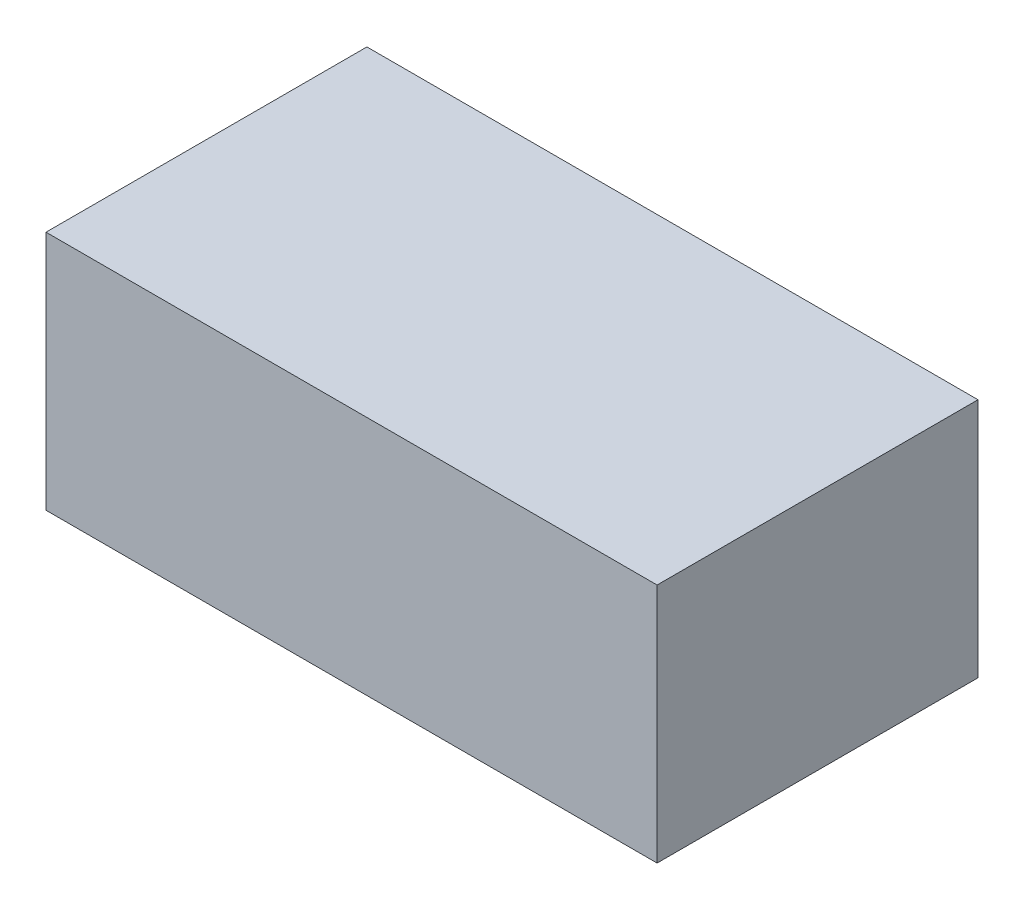
SolidWorks part; units mm, degrees
ref_plane "Plan de face" through (0, 0, 0) normal (0, 0, 1) x (1, 0, 0)
ref_plane "Plan de dessus" through (0, 0, 0) normal (0, 1, 0) x (1, 0, 0)
ref_plane "Plan de droite" through (0, 0, 0) normal (1, 0, 0) x (0, 0, -1)
sketch "Esquisse1" plane through (0, 0, 0) normal (0, 1, 0) x (1, 0, 0)
  line L1 (5.075, -2.665) -> (-5.075, -2.665)
  line L2 (5.075, -2.665) -> (5.075, 2.665)
  line L3 (5.075, 2.665) -> (-5.075, 2.665)
  line L4 (-5.075, -2.665) -> (-5.075, 2.665)
  line L5 (5.075, -2.665) -> (-5.075, 2.665) construction
  line L6 (5.075, 2.665) -> (-5.075, -2.665) construction
  point P0 (0, 0)
  dimension "D1" = 10.15
  dimension "D2" = 5.33
extrude "Boss.-Extru.1" add sketch "Esquisse1" along normal blind 4
